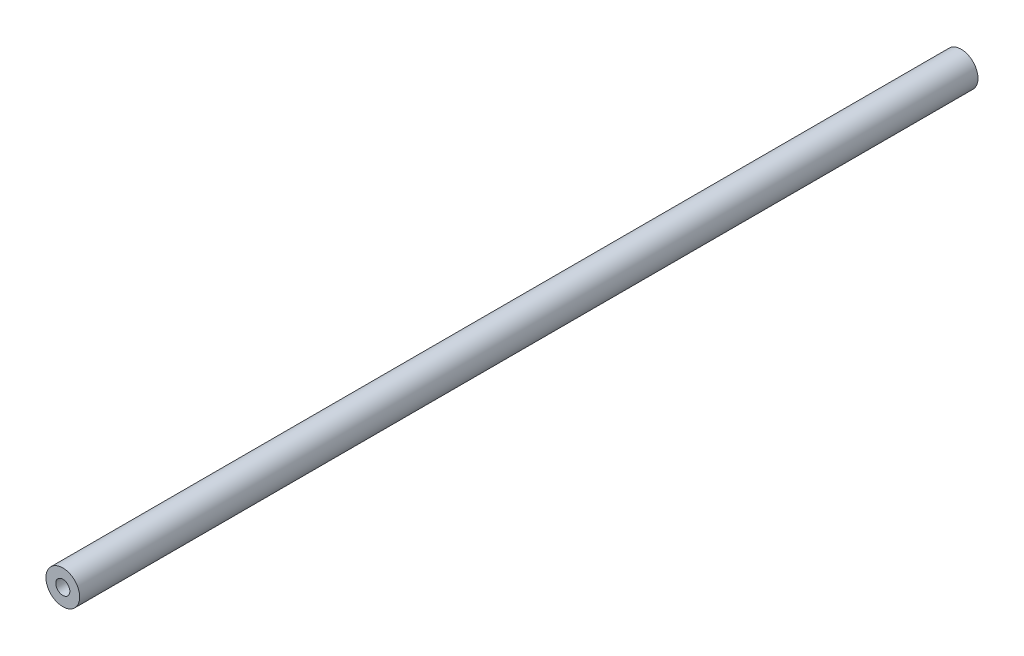
SolidWorks part; units mm, degrees
material "铸造碳钢"
ref_plane "前视基准面" through (0, 0, 0) normal (0, 0, 1) x (1, 0, 0)
ref_plane "上视基准面" through (0, 0, 0) normal (0, 1, 0) x (1, 0, 0)
ref_plane "右视基准面" through (0, 0, 0) normal (1, 0, 0) x (0, 0, -1)
sketch "草图1" plane through (0, 0, 0) normal (0, 0, 1) x (1, 0, 0)
  circle A0 centre (0, 0) radius 0.0005
  circle A1 centre (0, 0) radius 6
  dimension "D1" = 12
  dimension "D2" = 0.001
extrude "凸台-拉伸1" add sketch "草图1" against normal blind 320
sketch "草图2" plane through (0, 0, 0) normal (0, 0, 1) x (1, 0, 0)
  circle A0 centre (0, 0) radius 2.5
  dimension "D1" = 5
extrude "切除-拉伸1" cut sketch "草图2" against normal through all
